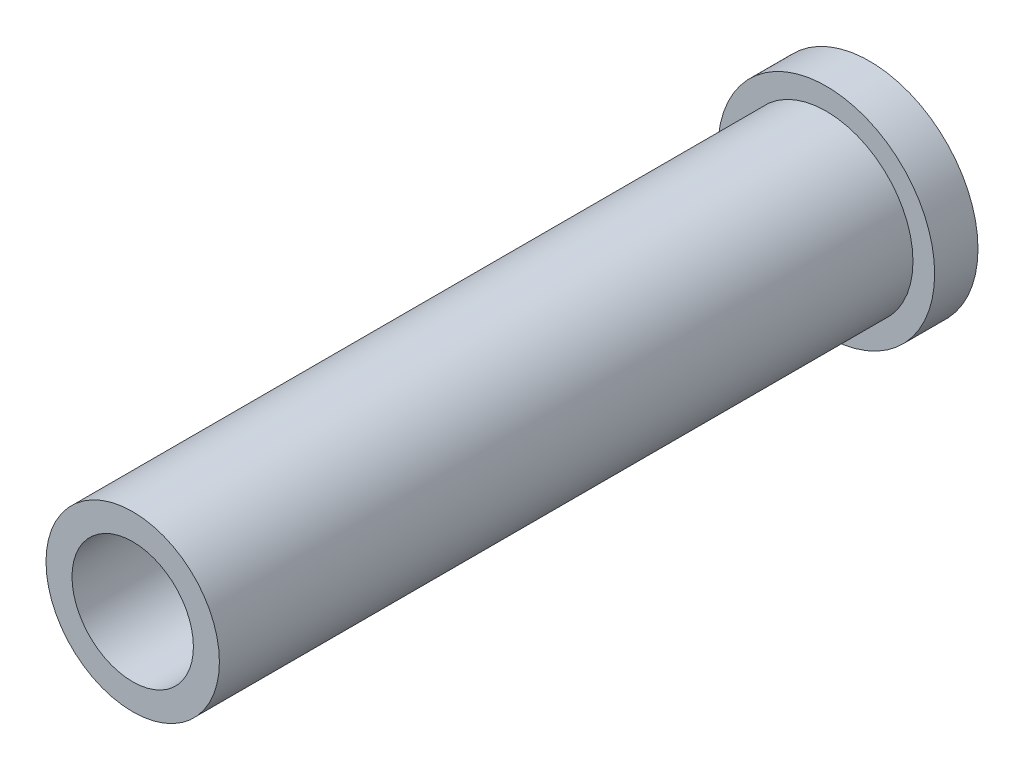
SolidWorks part; units mm, degrees
ref_plane "前视基准面" through (0, 0, 0) normal (0, 0, 1) x (1, 0, 0)
ref_plane "上视基准面" through (0, 0, 0) normal (0, 1, 0) x (1, 0, 0)
ref_plane "右视基准面" through (0, 0, 0) normal (1, 0, 0) x (0, 0, -1)
other "Configuration Table"
sketch "草图1" plane through (0, 0, 0) normal (0, 0, 1) x (1, 0, 0)
  circle A1 centre (0, 0) radius 2
  circle A2 centre (0, 0) radius 1.4
  dimension "D1" = 4
  dimension "D2" = 2.8
extrude "凸台-拉伸1" add sketch "草图1" along normal blind 16
sketch "草图2" plane through (0, 0, 0) normal (0, 0, -1) x (-1, 0, 0)
  circle A0 centre (0, 0) radius 2.5
  dimension "D1" = 5
extrude "凸台-拉伸2" add sketch "草图2" along normal blind 1
sketch "草图3" plane through (0, 0, -1) normal (0, 0, -1) x (-1, 0, 0)
  circle A0 centre (0, 0) radius 1.4
  circle A2 centre (0, 0) radius 1.4 construction
extrude "切除-拉伸1" cut sketch "草图3" against normal up to next
